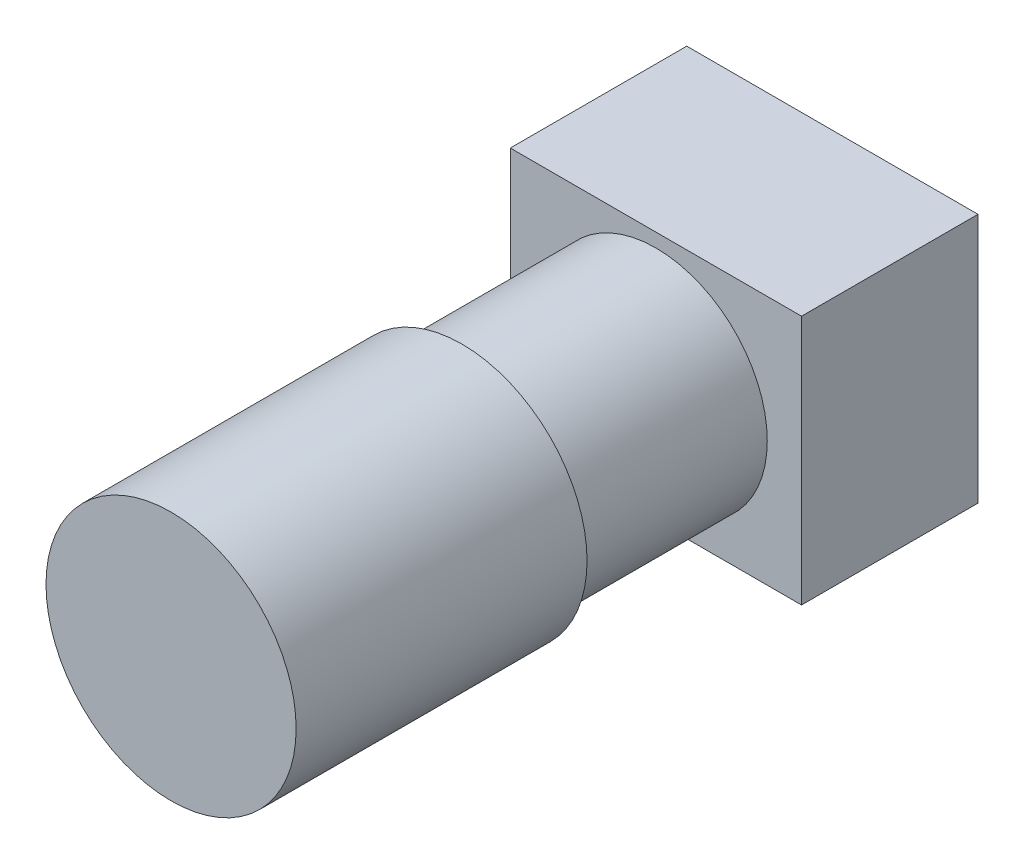
SolidWorks part; units mm, degrees
ref_plane "Front Plane" through (0, 0, 0) normal (0, 0, 1) x (1, 0, 0)
ref_plane "Top Plane" through (0, 0, 0) normal (0, 1, 0) x (1, 0, 0)
ref_plane "Right Plane" through (0, 0, 0) normal (1, 0, 0) x (0, 0, -1)
sketch "Sketch1" plane through (0, 0, 0) normal (0, 0, 1) x (1, 0, 0)
  line L1 (-85, -73) -> (85, -73)
  line L2 (-85, -73) -> (-85, 73)
  line L3 (-85, 73) -> (85, 73)
  line L4 (85, -73) -> (85, 73)
  line L5 (-85, -73) -> (85, 73) construction
  line L6 (-85, 73) -> (85, -73) construction
  point P0 (0, 0)
  dimension "D1" = 170
  dimension "D2" = 146
extrude "Boss-Extrude1" add sketch "Sketch1" along normal blind 103
sketch "Sketch2" plane through (0, 0, 103) normal (0, 0, 1) x (1, 0, 0)
  circle A0 centre (0, 0) radius 65
  dimension "D1" = 130
extrude "Boss-Extrude2" add sketch "Sketch2" along normal blind 113.2
sketch "Sketch3" plane through (0, 0, 216.2) normal (0, 0, 1) x (1, 0, 0)
  circle A0 centre (0, 0) radius 73
  dimension "D1" = 146
extrude "Boss-Extrude3" add sketch "Sketch3" along normal blind 169.8
